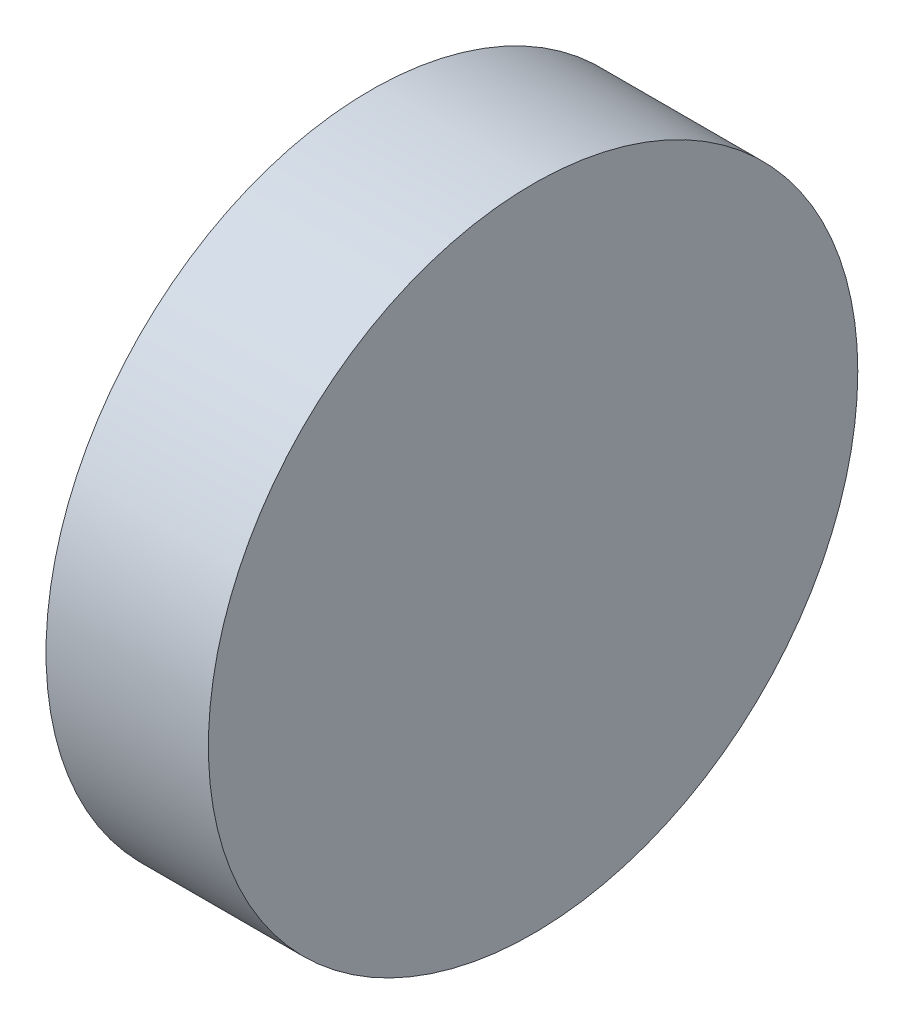
SolidWorks part; units mm, degrees
ref_plane "Front Plane" through (0, 0, 0) normal (0, 0, 1) x (1, 0, 0)
ref_plane "Top Plane" through (0, 0, 0) normal (0, 1, 0) x (1, 0, 0)
ref_plane "Right Plane" through (0, 0, 0) normal (1, 0, 0) x (0, 0, -1)
sketch "Sketch1" plane through (0, 0, 0) normal (1, 0, 0) x (0, 0, -1)
  circle A0 centre (0, 0) radius 20
  dimension "D1" = 40
extrude "Boss-Extrude1" add sketch "Sketch1" along normal blind 10
hole_wizard "M2x0.4 Tapped Hole1" positions "Sketch2" profile "Sketch3" tap size "M2x0.4" standard "ANSI Metric"
sketch "Sketch2" plane through (0, 0, 0) normal (-1, 0, 0) x (0, 0, 1)
  point P5 (0, -5)
sketch "Sketch3" plane through (0, -5, 0) normal (0, 1, 0) x (0, 0, 1)
  line L0 (0, 0) -> (0, 5.6807)
  line L1 (0, 5.6807) -> (0.8, 5.2)
  line L2 (0.8, 5.2) -> (0.8, 0.225)
  line L3 (0.8, 0.225) -> (1.025, 0)
  line L5 (1.025, 0) -> (0, 0)
  line L6 (-0.8, 0.225) -> (-1.025, 0) construction
  line L10 (0, 5.6807) -> (-0.8, 5.2) construction
  line L11 (0, -6.35) -> (0, 107.95) construction
  dimension "Tap Drill Dia." = 1.6
  dimension "Tap Drill Depth" = 5.2
  dimension "Near C'Sink Dia." = 2.05
  dimension "Near C'Sink Angle" = 90
  dimension "Drill Angle" = 118
cosmetic thread "Hole Thread1"
